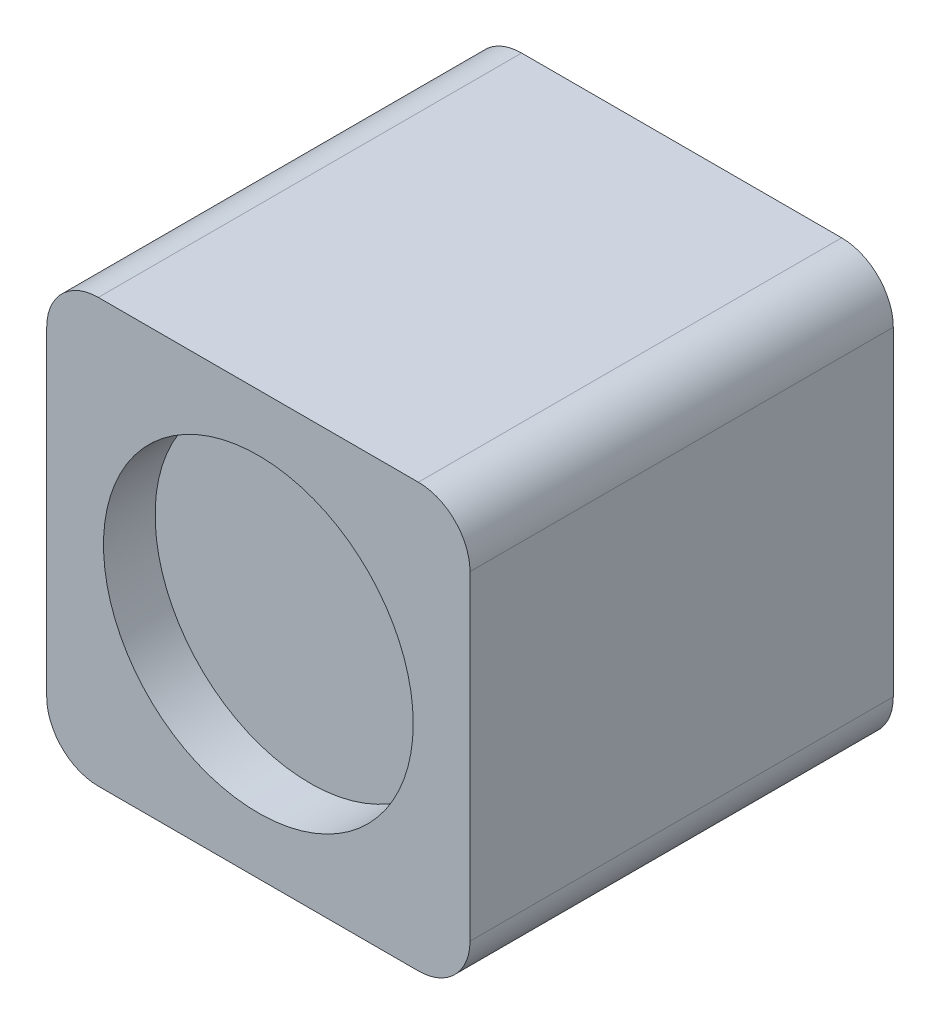
SolidWorks part; units mm, degrees
ref_plane "前视基准面" through (0, 0, 0) normal (0, 0, 1) x (1, 0, 0)
ref_plane "上视基准面" through (0, 0, 0) normal (0, 1, 0) x (1, 0, 0)
ref_plane "右视基准面" through (0, 0, 0) normal (1, 0, 0) x (0, 0, -1)
sketch "草图1" plane through (0, 0, 0) normal (0, 0, 1) x (1, 0, 0)
  line L1 (-20.5, 20.5) -> (20.5, 20.5)
  line L2 (-20.5, 20.5) -> (-20.5, -20.5)
  line L3 (-20.5, -20.5) -> (20.5, -20.5)
  line L4 (20.5, 20.5) -> (20.5, -20.5)
  line L5 (-20.5, 20.5) -> (20.5, -20.5) construction
  line L6 (-20.5, -20.5) -> (20.5, 20.5) construction
  point P0 (0, 0)
  dimension "D1" = 41
  dimension "D2" = 41
extrude "凸台-拉伸1" add sketch "草图1" along normal blind 41
sketch "草图2" plane through (0, 0, 41) normal (0, 0, 1) x (1, 0, 0)
  circle A0 centre (0, 0) radius 15
  dimension "D1" = 30
extrude "切除-拉伸1" cut sketch "草图2" against normal blind 5
fillet "圆角1" radius 5 4 edges at (-20.5, -20.5, 20.5) (20.5, -20.5, 20.5) (20.5, 20.5, 20.5) (-20.5, 20.5, 20.5)
